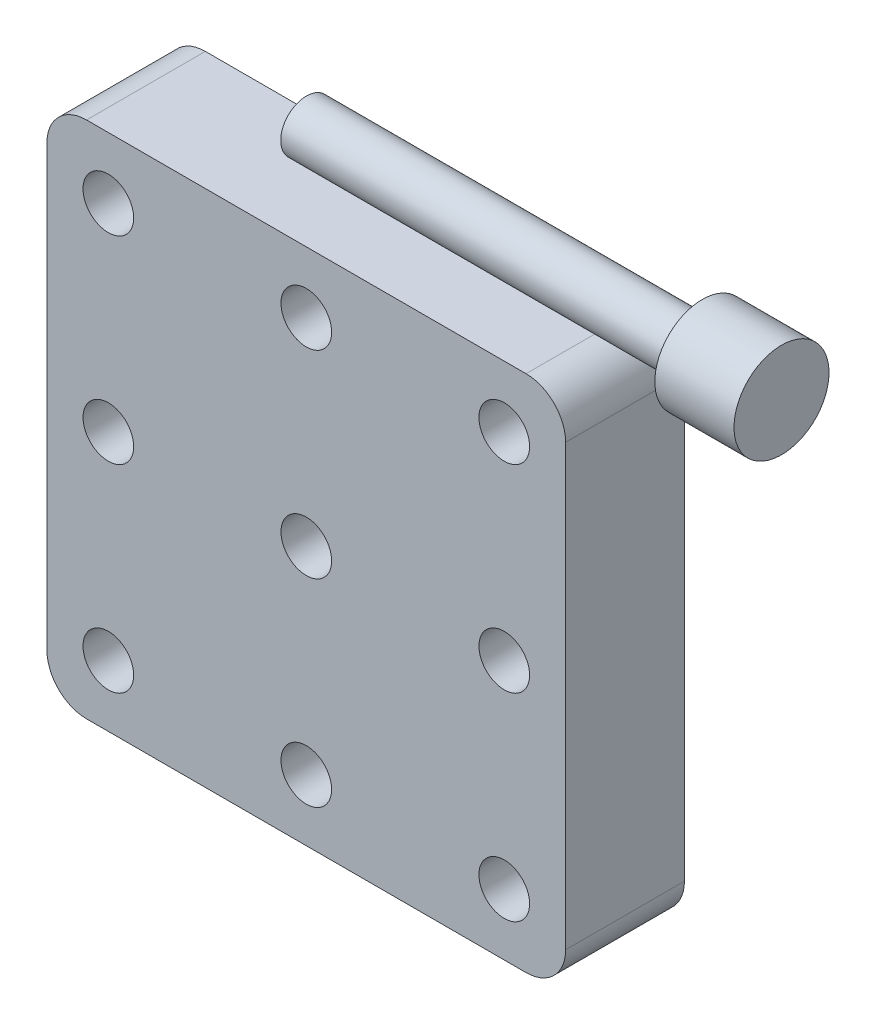
SolidWorks part; units mm, degrees
ref_plane "정면" through (0, 0, 0) normal (0, 0, 1) x (1, 0, 0)
ref_plane "윗면" through (0, 0, 0) normal (0, 1, 0) x (1, 0, 0)
ref_plane "우측면" through (0, 0, 0) normal (1, 0, 0) x (0, 0, -1)
sketch "스케치1" plane through (0, 0, 0) normal (0, 0, 1) x (1, 0, 0)
  line L1 (-32.75, -32.75) -> (32.75, -32.75)
  line L2 (-32.75, -32.75) -> (-32.75, 32.75)
  line L3 (-32.75, 32.75) -> (32.75, 32.75)
  line L4 (32.75, -32.75) -> (32.75, 32.75)
  line L5 (-32.75, -32.75) -> (32.75, 32.75) construction
  line L6 (-32.75, 32.75) -> (32.75, -32.75) construction
  point P0 (0, 0)
extrude "보스-돌출1" add sketch "스케치1" along normal blind 20 contours L3 L4 L1 L2
fillet "필렛1" radius 5 4 edges at (-32.75, -32.75, 10) (32.75, -32.75, 10) (32.75, 32.75, 10) (-32.75, 32.75, 10)
sketch "스케치3" plane through (0, 0, 20) normal (0, 0, 1) x (1, 0, 0)
  line L0 (-25, 0) -> (7.75, 0) construction
  line L1 (0, 0) -> (32.75, 0) construction
  line L2 (32.75, -27.75) -> (32.75, 27.75) construction
  line L3 (-50, 0) -> (-17.25, 0) construction
  circle A0 centre (25, -25) radius 3.2
  circle A1 centre (25, 25) radius 3.2
  circle A2 centre (25, 0) radius 3.2
  circle A3 centre (0, -25) radius 3.2
  circle A4 centre (0, 25) radius 3.2
  circle A5 centre (0, 0) radius 3.2
  circle A6 centre (-25, -25) radius 3.2
  circle A7 centre (-25, 25) radius 3.2
  circle A8 centre (-25, 0) radius 3.2
  dimension "D1" = 25
  dimension "D5" = 3
  dimension "D2" = 25
  dimension "D3" = 7.75
  dimension "D4" = 7.75
sketch "스케치5" plane through (0, 0, 0) normal (1, 0, 0) x (0, 0, -1)
  circle A0 centre (-9.988, 35.995) radius 3.245
extrude "보스-돌출2" add sketch "스케치5" along normal blind 40 and the other way blind 10 separate body
sketch "스케치6" plane through (40, 0, 0) normal (1, 0, 0) x (0, 0, -1)
  circle A0 centre (-9.988, 35.995) radius 6
extrude "보스-돌출3" add sketch "스케치6" along normal blind 10
sketch "스케치7" plane through (0, 0, 0) normal (0, 0, -1) x (-1, 0, 0)
  line L0 (32.75, 0) -> (-32.75, 0) construction
  line L1 (32.75, -27.75) -> (32.75, 27.75) construction
  line L2 (-32.75, -27.75) -> (-32.75, 27.75) construction
  circle A0 centre (-25, -25) radius 3.2
  circle A1 centre (-25, 25) radius 3.2
  dimension "D1" = 25
  dimension "D2" = 25
  dimension "D3" = 7.75
  dimension "D4" = 7.75
extrude "컷-돌출2" cut sketch "스케치7" against normal blind 5
extrude "컷-돌출3" cut sketch "스케치3" against normal blind 15
sketch "스케치9" plane through (0, 0, 0) normal (0, 0, -1) x (-1, 0, 0)
  line L1 (-32.75, 32.75) -> (32.75, 32.75)
  line L2 (-32.75, 32.75) -> (-32.75, -32.75)
  line L3 (-32.75, -32.75) -> (32.75, -32.75)
  line L4 (32.75, 32.75) -> (32.75, -32.75)
  line L5 (-32.75, 32.75) -> (32.75, -32.75) construction
  line L6 (-32.75, -32.75) -> (32.75, 32.75) construction
  point P0 (0, 0)
extrude "컷-돌출5" cut sketch "스케치9" against normal blind 5
